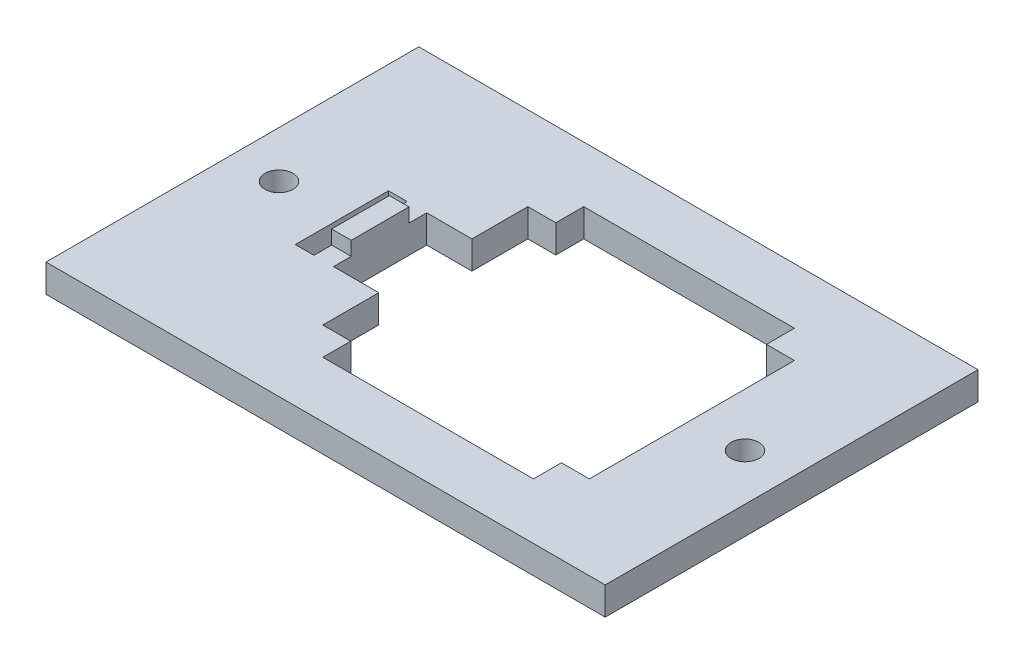
SolidWorks part; units mm, degrees
ref_plane "Front Plane" through (0, 0, 0) normal (0, 0, 1) x (1, 0, 0)
ref_plane "Top Plane" through (0, 0, 0) normal (0, 1, 0) x (1, 0, 0)
ref_plane "Right Plane" through (0, 0, 0) normal (1, 0, 0) x (0, 0, -1)
sketch "Sketch1" plane through (0, 0, 0) normal (0, 1, 0) x (1, 0, 0)
  line L1 (30, -20) -> (-30, -20)
  line L2 (30, -20) -> (30, 20)
  line L3 (30, 20) -> (-30, 20)
  line L4 (-30, -20) -> (-30, 20)
  line L5 (30, -20) -> (-30, 20) construction
  line L6 (30, 20) -> (-30, -20) construction
  point P0 (0, 0)
  dimension "D1" = 60
  dimension "D2" = 40
extrude "MainBody" add sketch "Sketch1" along normal blind 3
sketch "Sketch2" plane through (0, 3, 0) normal (0, 1, 0) x (1, 0, 0)
  line L0 (30, -20) -> (30, 20) construction
  line L1 (19.3, -14) -> (-9.3, -14)
  line L2 (19.3, -14) -> (19.3, 14)
  line L3 (19.3, 14) -> (-9.3, 14)
  line L4 (-9.3, -14) -> (-9.3, 14)
  line L5 (19.3, -14) -> (-9.3, 14) construction
  line L6 (19.3, 14) -> (-9.3, -14) construction
  point P0 (5, 0)
  dimension "D1" = 10.7
  dimension "D2" = 28
  dimension "D3" = 28.6
extrude "Cut-Extrude1" cut sketch "Sketch2" against normal up to next
sketch "Sketch7" plane through (0, 3, 0) normal (0, 1, 0) x (1, 0, 0)
  line L0 (-9.3, 14) -> (-9.3, -14) construction
  line L1 (19.3, -14) -> (19.3, 14) construction
  circle A0 centre (25, 0) radius 1.5
  circle A1 centre (-25, 0) radius 1.5
  dimension "D1" = 3
  dimension "D2" = 3
  dimension "D3" = 15.7
  dimension "D4" = 5.7
extrude "Cut-Extrude2" cut sketch "Sketch7" against normal up to next
sketch "Sketch8" plane through (0, 3, 0) normal (0, 1, 0) x (1, 0, 0)
  line L1 (-9.3, 14) -> (-6.3, 14)
  line L2 (-9.3, 14) -> (-9.3, 11)
  line L3 (-9.3, 11) -> (-6.3, 11)
  line L4 (-6.3, 14) -> (-6.3, 11)
  line L5 (-9.3, -14) -> (-6.3, -14)
  line L6 (-9.3, -14) -> (-9.3, -11)
  line L7 (-9.3, -11) -> (-6.3, -11)
  line L8 (-6.3, -14) -> (-6.3, -11)
  line L9 (19.3, -14) -> (16.3, -14)
  line L10 (19.3, -14) -> (19.3, -11)
  line L11 (19.3, -11) -> (16.3, -11)
  line L12 (16.3, -14) -> (16.3, -11)
  line L13 (19.3, 14) -> (16.3, 14)
  line L14 (19.3, 14) -> (19.3, 11)
  line L15 (19.3, 11) -> (16.3, 11)
  line L16 (16.3, 14) -> (16.3, 11)
  dimension "D1" = 3
  dimension "D2" = 3
  dimension "D3" = 3
  dimension "D4" = 3
  dimension "D5" = 3
  dimension "D6" = 3
  dimension "D7" = 3
  dimension "D8" = 3
extrude "Boss-Extrude2" add sketch "Sketch8" against normal up to surface (3 mm away) up to face at (25, 0, 1.5)
sketch "Sketch9" plane through (0, 3, 0) normal (0, 1, 0) x (1, 0, 0)
  line L0 (-9.3, 11) -> (-9.3, -11) construction
  line L1 (-9.3, -5) -> (-14.15, -5)
  line L2 (-9.3, -5) -> (-9.3, 5)
  line L3 (-9.3, 5) -> (-14.15, 5)
  line L4 (-18.25, -5) -> (-18.25, 5)
  line L5 (-15.2, 5) -> (-15.2, -5) construction
  line L7 (-16.25, 5) -> (-16.25, -5)
  line L9 (-14.15, 5) -> (-14.15, -5)
  line L10 (-16.25, 5) -> (-18.25, 5)
  line L11 (-16.25, -5) -> (-18.25, -5)
  point P6 (-18.25, 0)
  dimension "D1" = 10
  dimension "D2" = 8.95
  dimension "D3" = 5.9
  dimension "D4" = 2.1
extrude "Cut-Extrude3" cut sketch "Sketch9" against normal up to next
sketch "Sketch10" plane through (0, 3, 0) normal (0, 1, 0) x (1, 0, 0)
  line L0 (-16.25, -5) -> (-16.25, 5) construction
  line L1 (-16.25, 3.1) -> (-14.15, 3.1)
  line L2 (-16.25, 3.1) -> (-16.25, -3.1)
  line L3 (-16.25, -3.1) -> (-14.15, -3.1)
  line L4 (-14.15, 3.1) -> (-14.15, -3.1)
  line L5 (-14.15, 5) -> (-14.15, -5) construction
  line L6 (-14.15, 0) -> (-16.25, 0) construction
  dimension "D1" = 6.2
extrude "Boss-Extrude3" add sketch "Sketch10" along normal blind 1.5
